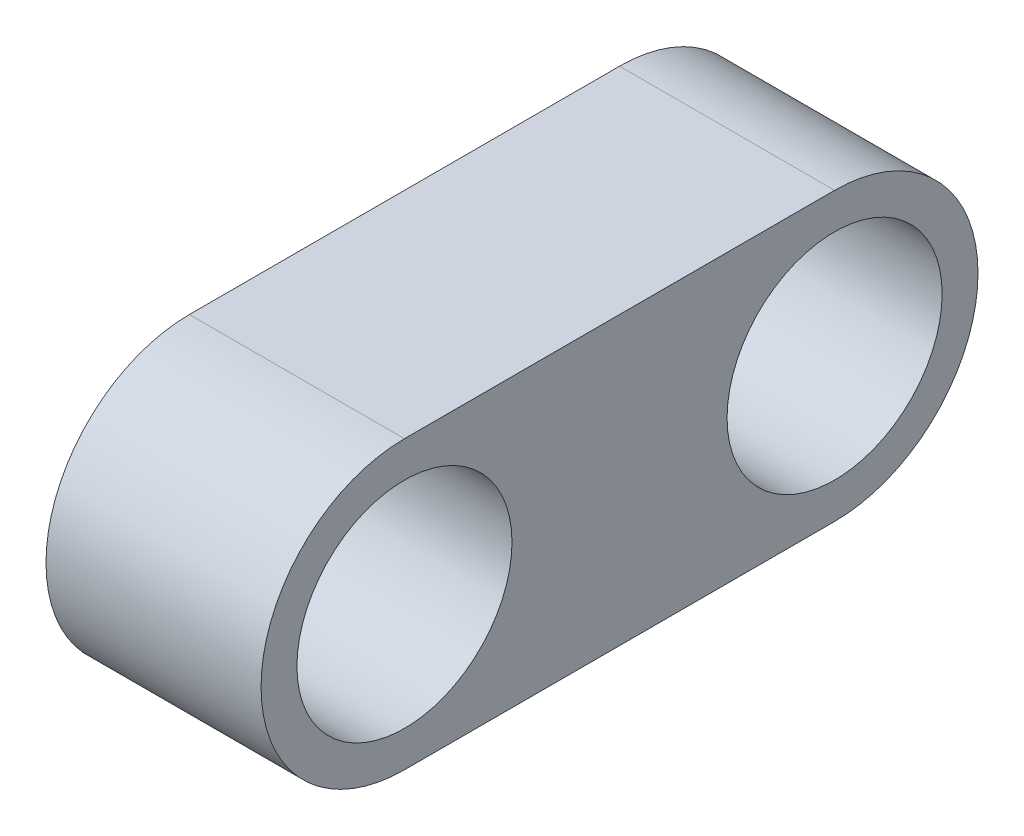
SolidWorks part; units mm, degrees
material "Stainless Steel (ferritic)"
ref_plane "Front Plane" through (0, 0, 0) normal (0, 0, 1) x (1, 0, 0)
ref_plane "Top Plane" through (0, 0, 0) normal (0, 1, 0) x (1, 0, 0)
ref_plane "Right Plane" through (0, 0, 0) normal (1, 0, 0) x (0, 0, -1)
sketch "Sketch2" plane through (0, 0, 0) normal (1, 0, 0) x (0, 0, -1)
  line L0 (0, 0) -> (6, 0)
  line L1 (0, -4) -> (6, -4)
  line L2 (-2, -2) -> (8, -2) construction
  circle A0 centre (6, -2) radius 2
  circle A1 centre (0, -2) radius 2
  circle A2 centre (0, -2) radius 1.5
  circle A3 centre (6, -2) radius 1.5
  dimension "D1" = 10
  dimension "D2" = 4
  dimension "D3" = 3
  dimension "D4" = 3
extrude "Boss-Extrude1" add sketch "Sketch2" along normal blind 3 contours A1 L2 A0 L0 | L2 A1 L1 A0 | L2 A1 A2 | A1 L2 A2 | L2 A0 A3 | A0 L2 A3
